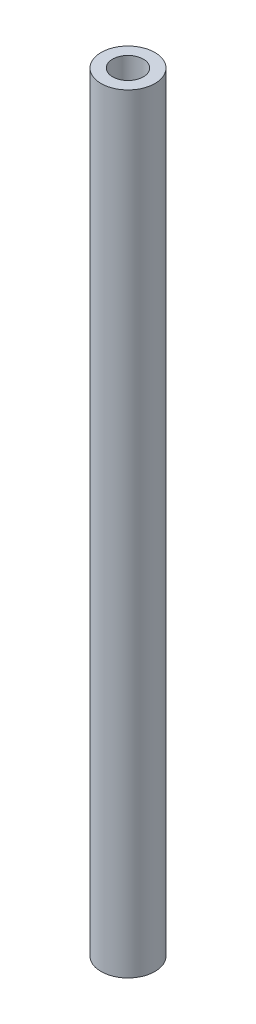
SolidWorks part; units mm, degrees
ref_plane "前视基准面" through (0, 0, 0) normal (0, 0, 1) x (1, 0, 0)
ref_plane "上视基准面" through (0, 0, 0) normal (0, 1, 0) x (1, 0, 0)
ref_plane "右视基准面" through (0, 0, 0) normal (1, 0, 0) x (0, 0, -1)
other "Configuration Table"
sketch "草图1" plane through (0, 0, 0) normal (0, 1, 0) x (1, 0, 0)
  circle A0 centre (0, 0) radius 1.75
  circle A1 centre (0, 0) radius 1
  dimension "D1" = 3.5
  dimension "D2" = 2
extrude "凸台-拉伸1" add sketch "草图1" along normal blind 50
